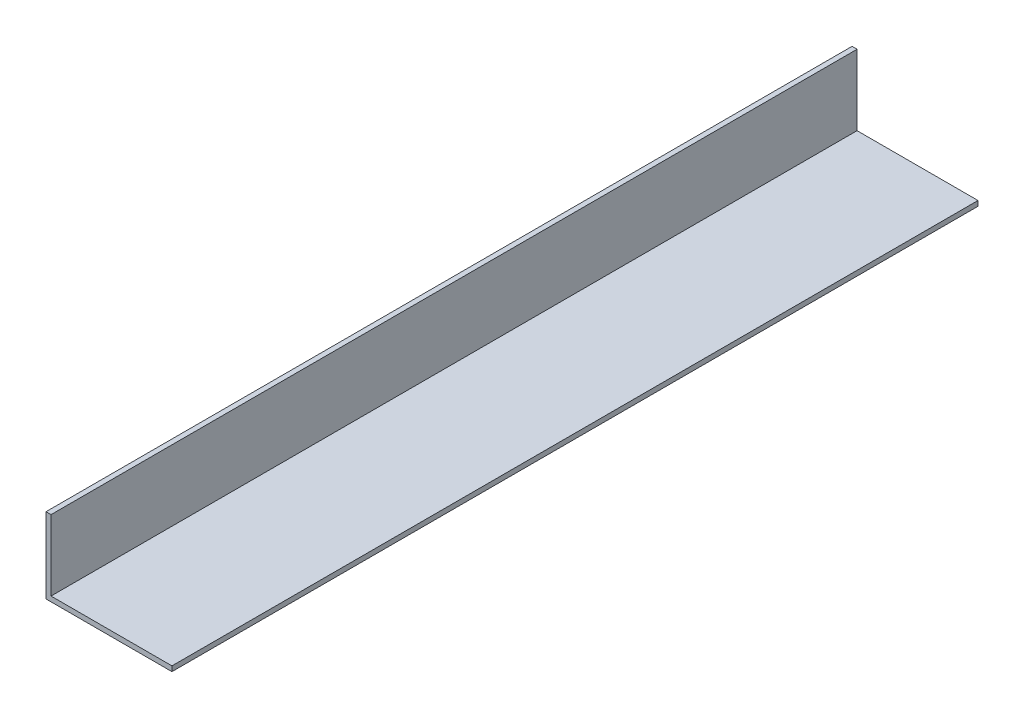
SolidWorks part; units mm, degrees
ref_plane "Front Plane" through (0, 0, 0) normal (0, 0, 1) x (1, 0, 0)
ref_plane "Top Plane" through (0, 0, 0) normal (0, 1, 0) x (1, 0, 0)
ref_plane "Right Plane" through (0, 0, 0) normal (1, 0, 0) x (0, 0, -1)
sketch "Sketch1" plane through (0, 0, 0) normal (0, 0, 1) x (1, 0, 0)
  line L0 (0, 0) -> (0, 30)
  line L1 (0, 30) -> (2, 30)
  line L2 (2, 30) -> (2, 2)
  line L3 (2, 2) -> (50, 2)
  line L4 (50, 2) -> (50, 0)
  line L5 (50, 0) -> (0, 0)
extrude "Boss-Extrude1" add sketch "Sketch1" along normal blind 320
